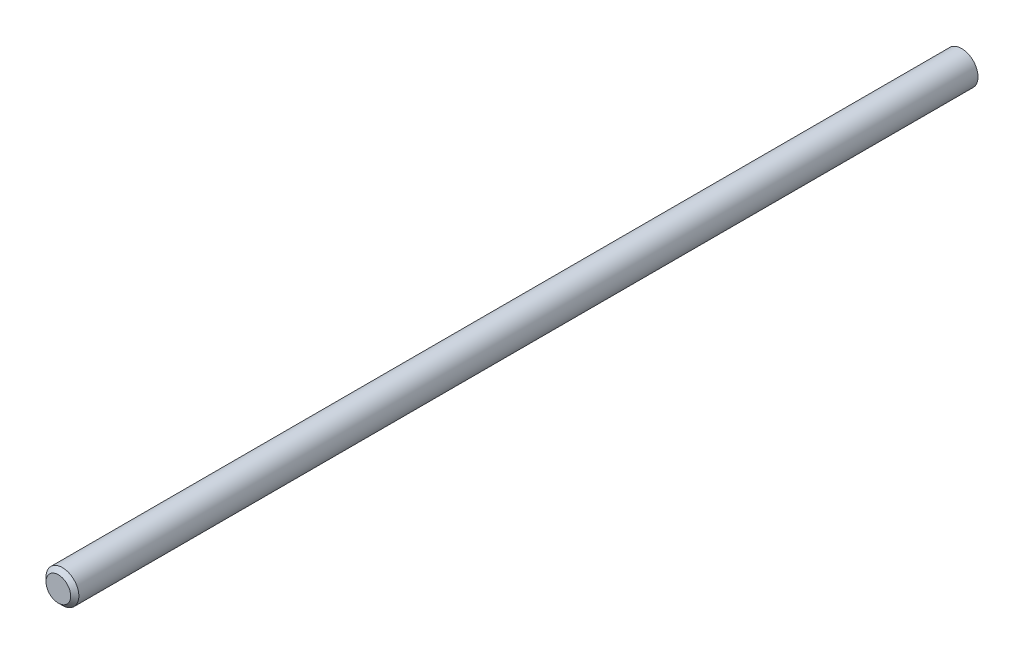
SolidWorks part; units mm, degrees
material "AISI 304"
ref_plane "前视基准面" through (0, 0, 0) normal (0, 0, 1) x (1, 0, 0)
ref_plane "上视基准面" through (0, 0, 0) normal (0, 1, 0) x (1, 0, 0)
ref_plane "右视基准面" through (0, 0, 0) normal (1, 0, 0) x (0, 0, -1)
sketch "草图1" plane through (0, 0, 0) normal (0, 0, 1) x (1, 0, 0)
  circle A0 centre (0, 0) radius 4
  dimension "D1" = 8
extrude "凸台-拉伸1" add sketch "草图1" along normal blind 220
chamfer "倒角1" distance 1 angle 45 1 edges at (4, 0, 220)
